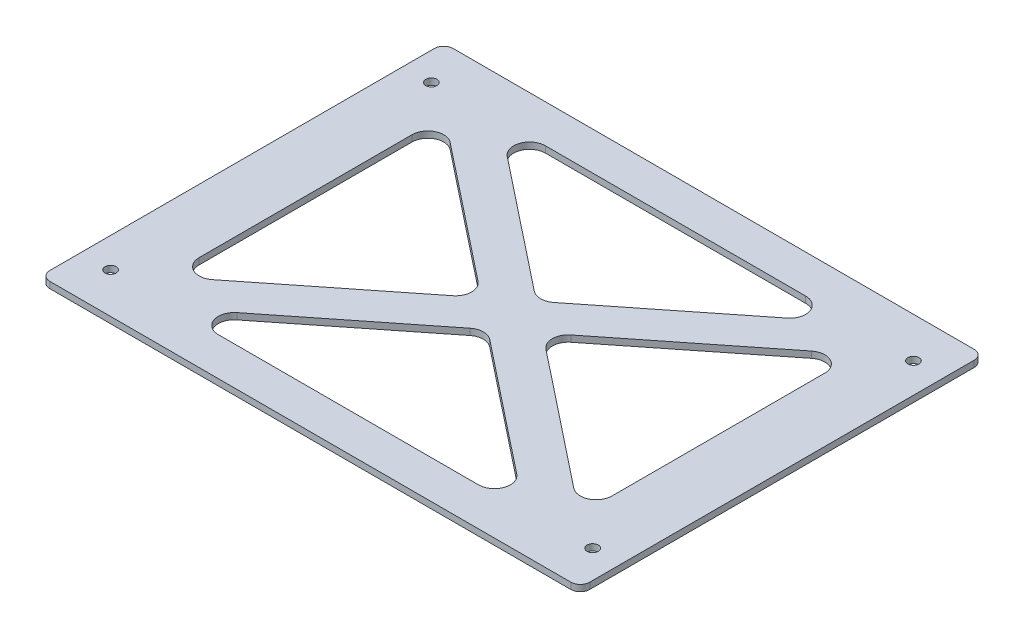
SolidWorks part; units mm, degrees
ref_plane "Front Plane" through (0, 0, 0) normal (0, 0, 1) x (1, 0, 0)
ref_plane "Top Plane" through (0, 0, 0) normal (0, 1, 0) x (1, 0, 0)
ref_plane "Right Plane" through (0, 0, 0) normal (1, 0, 0) x (0, 0, -1)
sketch "Sketch1" plane through (0, 0, 0) normal (0, 1, 0) x (1, 0, 0)
  line L1 (-84.2086, 56.5444) -> (85.7914, 56.5444)
  line L2 (-84.2086, 56.5444) -> (-84.2086, -70.4556)
  line L3 (-84.2086, -70.4556) -> (85.7914, -70.4556)
  line L4 (85.7914, 56.5444) -> (85.7914, -70.4556)
  line L5 (-54.5469, 44.5444) -> (56.1298, 44.5444)
  line L6 (-64.2086, 36.8894) -> (-64.2086, -50.8006)
  line L7 (-54.5469, -58.4556) -> (56.1298, -58.4556)
  line L8 (65.7914, 36.8894) -> (65.7914, -50.8006)
  line L10 (-64.2086, 36.8894) -> (-8.8702, -6.9556)
  line L11 (-54.5469, 44.5444) -> (0.7914, 0.6994)
  line L12 (56.1298, 44.5444) -> (0.7914, 0.6994)
  line L13 (65.7914, 36.8894) -> (10.4531, -6.9556)
  line L14 (10.4531, -6.9556) -> (65.7914, -50.8006)
  line L15 (0.7914, -14.6106) -> (56.1298, -58.4556)
  line L16 (0.7914, -14.6106) -> (-54.5469, -58.4556)
  line L17 (-8.8702, -6.9556) -> (-64.2086, -50.8006)
  dimension "D1" = 170
  dimension "D2" = 127
  dimension "D3" = 12
  dimension "D4" = 12
  dimension "D5" = 20
  dimension "D6" = 20
extrude "Boss-Extrude1" add sketch "Sketch1" along normal blind 2
fillet "Fillet1" radius 5 11 edges at (-8.8702, 1, 6.9556) (10.4531, 1, 6.9556) (0.7914, 1, 14.6106) (0.7914, 1, -0.6994) (56.1298, 1, 58.4556) (65.7914, 1, 50.8006) (65.7914, 1, -36.8894) (-64.2086, 1, 50.8006) (-64.2086, 1, -36.8894) (56.1298, 1, -44.5444) (-54.5469, 1, -44.5444)
fillet "Fillet2" radius 3 4 edges at (-84.2086, 1, 70.4556) (85.7914, 1, 70.4556) (85.7914, 1, -56.5444) (-84.2086, 1, -56.5444)
sketch "Sketch2" plane through (0, 2, 0) normal (0, 1, 0) x (1, 0, 0)
  line L0 (-84.2086, 53.5444) -> (-84.2086, -67.4556) construction
  line L1 (82.7914, 56.5444) -> (-81.2086, 56.5444) construction
  circle A0 centre (-75.4086, 43.8444) radius 1.75
  circle A1 centre (76.3914, 43.8436) radius 1.75
  circle A2 centre (76.9914, -57.7546) radius 1.75
  circle A3 centre (-74.8086, -57.7539) radius 1.75
  dimension "D1" = 3.5
  dimension "D2" = 3.5
  dimension "D3" = 3.5
  dimension "D4" = 3.5
  dimension "D5" = 151.8
  dimension "D6" = 151.8
  dimension "D7" = 101.6
  dimension "D8" = 101.6
  dimension "D9" = 8.8
  dimension "D10" = 12.7
extrude "Cut-Extrude1" cut sketch "Sketch2" against normal blind 3
fillet "Fillet3" radius 5 1 edges at (-54.5469, 1, 58.4556)
